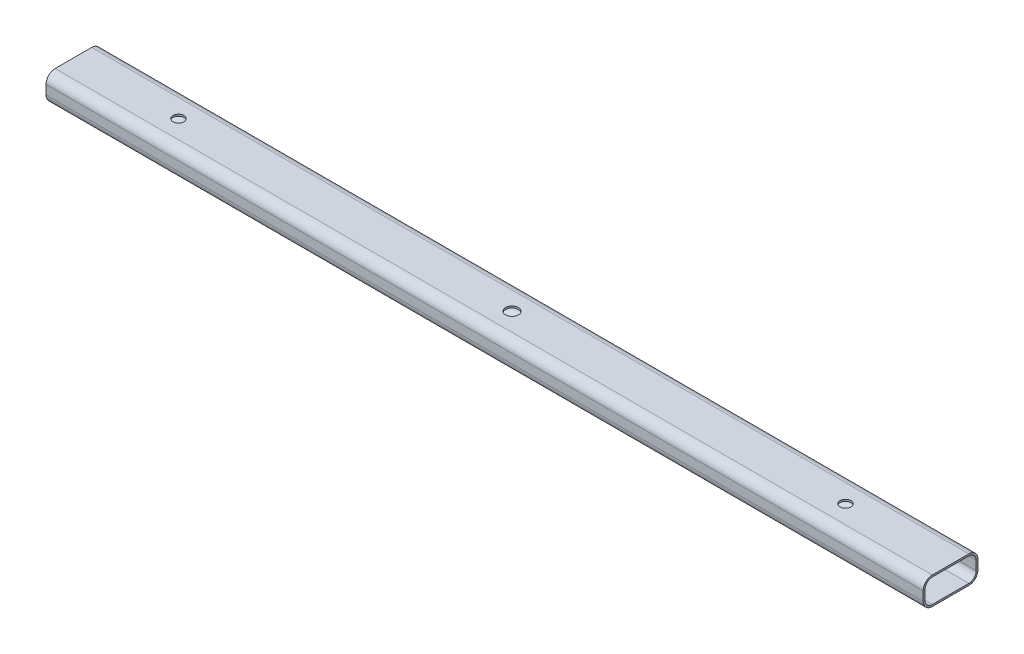
SolidWorks part; units mm, degrees
material "6063-T6"
ref_plane "Спереди" through (0, 0, 0) normal (0, 0, 1) x (1, 0, 0)
ref_plane "Сверху" through (0, 0, 0) normal (0, 1, 0) x (1, 0, 0)
ref_plane "Справа" through (0, 0, 0) normal (1, 0, 0) x (0, 0, -1)
sketch "Эскиз1" plane through (0, 0, 0) normal (1, 0, 0) x (0, 0, -1)
  line L1 (-10, -7.5) -> (10, -7.5)
  line L2 (-15, -2.5) -> (-15, 2.5)
  line L3 (-10, 7.5) -> (10, 7.5)
  line L4 (15, -2.5) -> (15, 2.5)
  line L5 (-15, -7.5) -> (15, 7.5) construction
  line L6 (-15, 7.5) -> (15, -7.5) construction
  arc A0 (-15, 2.5) -> (-10, 7.5) centre (-10, 2.5) cw
  arc A1 (-10, -7.5) -> (-15, -2.5) centre (-10, -2.5) cw
  arc A2 (10, -7.5) -> (15, -2.5) centre (10, -2.5) ccw
  arc A3 (10, 7.5) -> (15, 2.5) centre (10, 2.5) cw
  point P0 (0, 0)
  dimension "D3" = 5
  dimension "D1" = 30
  dimension "D2" = 15
extrude "Вытянуть-Тонкостенный1" add sketch "Эскиз1" along normal blind 480 thin thin type one direction reverse wall 1
sketch "Эскиз2" plane through (0, 7.5, 0) normal (0, 1, 0) x (1, 0, 0)
  line L0 (0, 0) -> (480, 0) construction
  line L1 (0, 10) -> (0, -10) construction
  line L2 (480, 10) -> (480, -10) construction
  line L3 (240, 0) -> (240, 29.8885) construction
  circle A0 centre (240, 0) radius 3.5
  circle A1 centre (57.5, 0) radius 3
  circle A2 centre (422.5, 0) radius 3
  dimension "D1" = 7
  dimension "D2" = 6
  dimension "D3" = 365
extrude "Вырез-Вытянуть1" cut sketch "Эскиз2" against normal through all
